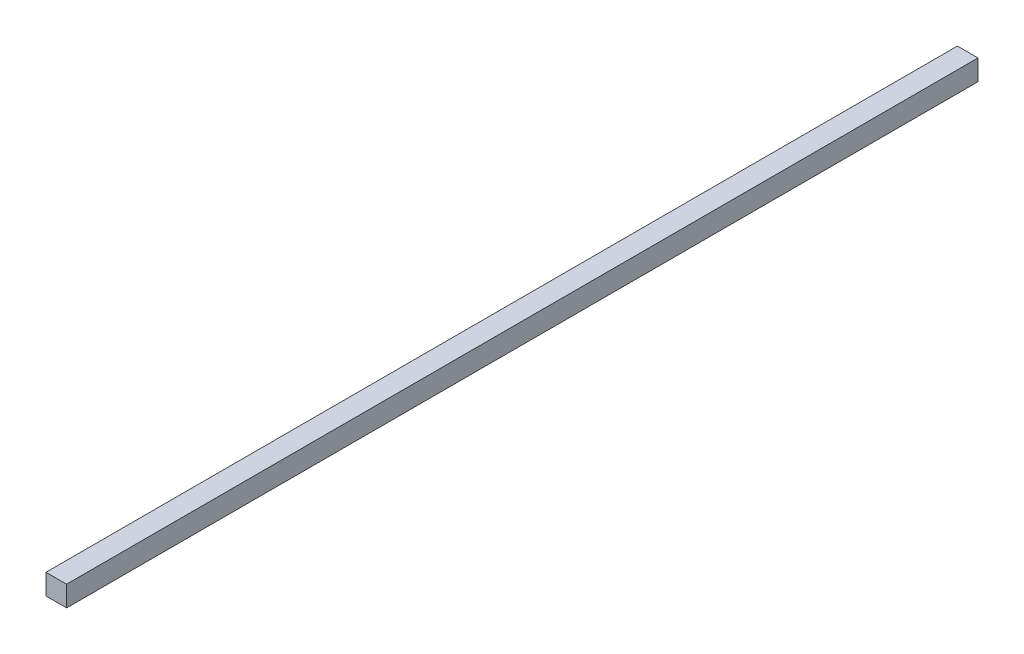
SolidWorks part; units mm, degrees
material "Pine"
ref_plane "Front Plane" through (0, 0, 0) normal (0, 0, 1) x (1, 0, 0)
ref_plane "Top Plane" through (0, 0, 0) normal (0, 1, 0) x (1, 0, 0)
ref_plane "Right Plane" through (0, 0, 0) normal (1, 0, 0) x (0, 0, -1)
sketch "Sketch1" plane through (0, 0, 0) normal (0, 0, 1) x (1, 0, 0)
  line L9 (744.8, -44.45) -> (694, -44.45)
  line L10 (744.8, -44.45) -> (744.8, 6.35)
  line L11 (744.8, 6.35) -> (694, 6.35)
  line L12 (694, -44.45) -> (694, 6.35)
  dimension "D1" = 50.8
  dimension "D2" = 50.8
extrude "Boss-Extrude1" add sketch "Sketch1" along normal up to surface (2247.9 mm away)
